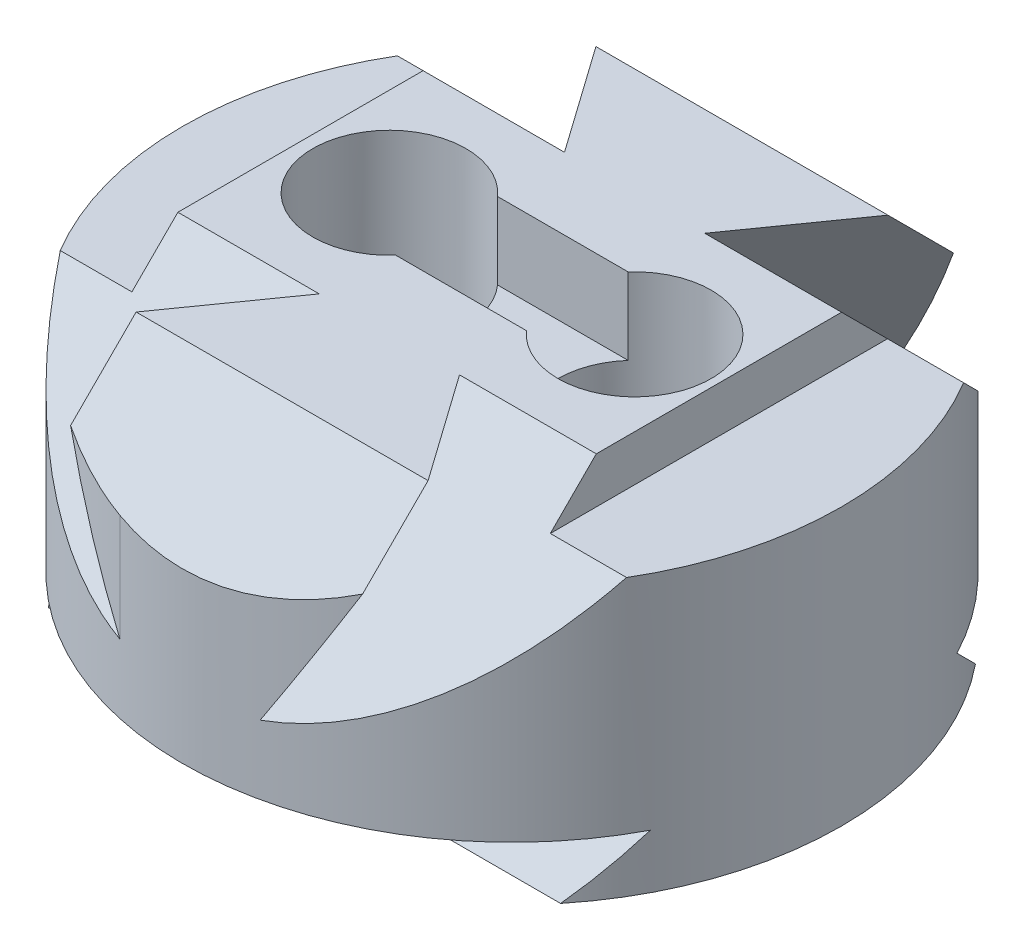
SolidWorks part; units mm, degrees
ref_plane "Front Plane" through (0, 0, 0) normal (0, 0, 1) x (1, 0, 0)
ref_plane "Top Plane" through (0, 0, 0) normal (0, 1, 0) x (1, 0, 0)
ref_plane "Right Plane" through (0, 0, 0) normal (1, 0, 0) x (0, 0, -1)
sketch "Sketch1" plane through (0, 0, 0) normal (0, 1, 0) x (1, 0, 0)
  circle A0 centre (0, 0) radius 21.5
  dimension "D1" = 43
extrude "Boss-Extrude1" add sketch "Sketch1" against normal blind 4
sketch "Sketch2" plane through (0, 0, 0) normal (0, 1, 0) x (1, 0, 0)
  circle A0 centre (0, 0) radius 5.875
  dimension "D1" = 11.75
extrude "Boss-Extrude2" add sketch "Sketch2" along normal blind 65
sketch "Sketch3" plane through (0, 0, 0) normal (0, 1, 0) x (1, 0, 0)
  line L0 (0, 0) -> (0, 21.5) construction
  line L1 (0, 21.5) -> (0, -21.5) construction
  circle A0 centre (0, 0) radius 21.5 construction
ref_plane "Plane1" through (0, 15.5, 0) normal (0, 1, 0) x (1, 0, 0)
sketch "Sketch5" plane through (0, 0, 0) normal (1, 0, 0) x (0, 0, -1)
  line L4 (21.5, 0) -> (-21.5, 0) construction
  line L5 (6, 0) -> (0, 0) construction
  line L8 (21.5, 0) -> (0, 0)
  line L10 (-21.5, 0) -> (0, 0)
  line L11 (21.5, 0) -> (6, 15.5)
  line L12 (23.65, 15.5) -> (-23.65, 15.5) construction
  line L13 (6, 15.5) -> (-6, 15.5)
  line L14 (-6, 15.5) -> (-21.5, 0)
  dimension "D1" = 21.5
  dimension "D2" = 15.5
  dimension "D3" = 15.5
extrude "Boss-Extrude3" add sketch "Sketch5" along normal up to surface and the other way up to surface up to face at (0, -4, 21.5) other way up to face at (0, -4, 21.5)
ref_plane "Plane2" through (0, 4.75, -4.75) normal (0, 0.7071, -0.7071) x (-1, 0, 0)
ref_plane "Plane3" through (0, 4.75, 4.75) normal (0, -0.7071, -0.7071) x (-1, 0, 0)
sketch "Sketch6" plane through (0, 4.75, 4.75) normal (0, -0.7071, -0.7071) x (-1, 0, 0)
  line L0 (0, 15.2028) -> (4.5753, 15.2028)
  line L1 (20.6458, 15.2028) -> (-20.6458, 15.2028) construction
  line L2 (4.5753, 15.2028) -> (9.525, 20.1525)
  line L3 (9.525, 20.1525) -> (0, 20.1525)
  line L4 (0, 20.1525) -> (-9.525, 20.1525)
  line L5 (-9.525, 20.1525) -> (-4.5753, 15.2028)
  line L6 (-4.5753, 15.2028) -> (0, 15.2028)
  dimension "D1" = 7
  dimension "D2" = 45
  dimension "D3" = 45
  dimension "D4" = 9.525
ref_plane "Plane4" through (0, 0, 6) normal (0, 0, 1) x (1, 0, 0)
ref_plane "Plane5" through (0, 0, -6) normal (0, 0, 1) x (1, 0, 0)
sketch "Sketch10" plane through (0, 4.75, -4.75) normal (0, 0.7071, -0.7071) x (-1, 0, 0)
  line L14 (0, 15.2028) -> (-4.5753, 15.2028)
  line L15 (20.6458, 15.2028) -> (-20.6458, 15.2028) construction
  line L16 (-4.5753, 15.2028) -> (-9.525, 20.1525)
  line L18 (9.525, 20.1525) -> (4.5753, 15.2028)
  line L19 (4.5753, 15.2028) -> (0, 15.2028)
  line L20 (9.525, 20.1525) -> (0, 20.1525)
  line L21 (0, 20.1525) -> (-9.525, 20.1525)
  dimension "D1" = 45
  dimension "D2" = 9.525
  dimension "D3" = 7
  dimension "D4" = 45
sketch "Sketch11" plane through (0, 0, 6) normal (0, 0, 1) x (1, 0, 0)
  line L0 (0, 65) -> (0, 15.5) construction
  line L1 (5.875, 65) -> (-5.875, 65) construction
  line L2 (0, 65) -> (0, 15.5) construction
sketch "Sketch12" plane through (0, 15.5, 0) normal (0, 1, 0) x (1, 0, 0)
  line L0 (-20.6458, 6) -> (20.6458, 6)
  line L1 (20.6458, -6) -> (-20.6458, -6)
  arc A0 (-20.6458, 6) -> (-20.6458, -6) centre (0, 0) ccw
  arc A2 (20.6458, 6) -> (20.6458, -6) centre (0, 0) cw
extrude "Boss-Extrude12" add sketch "Sketch6" along normal up to surface (21.9203 mm away) contours L3 L4 L5 L6 L0 L2
sketch "Sketch14" plane through (0, 15.5, 0) normal (0, 1, 0) x (1, 0, 0)
  circle A0 centre (0, 0) radius 5.875
  dimension "D1" = 11.75
ref_plane "Plane7" through (0, -4, 0) normal (0, -1, 0) x (-1, 0, 0)
sketch "Sketch17" plane through (0, 0, 0) normal (0, 0, 1) x (1, 0, 0)
  line L1 (-23.65, -4) -> (23.65, -4) construction
  line L2 (0, -4) -> (5, -4)
  line L3 (0, -4) -> (0, 6)
  line L4 (0, 6) -> (5, -4)
extrude "Boss-Extrude13" add sketch "Sketch10" against normal up to surface (13.8239 mm away) contours L21 L16 L14 L19 L18 L20
extrude "Cut-Extrude3" cut sketch "Sketch14" along normal blind 10 and the other way blind 2 flip side to cut contours A0
ref_plane "Plane8" through (0, 13.5, 0) normal (0, 1, 0) x (1, 0, 0)
sketch "Sketch18" plane through (0, 0, 0) normal (1, 0, 0) x (0, 0, -1)
  line L0 (0, -4) -> (21.5, -4)
  line L1 (-23.65, -4) -> (23.65, -4) construction
  line L2 (21.5, -4) -> (21.5, 7) construction
  line L3 (21.5, -4) -> (0, -49)
  line L4 (0, -49) -> (0, -4)
  dimension "D1" = 45
sketch "Sketch19" plane through (0, 13.5, 0) normal (0, 1, 0) x (1, 0, 0)
  line L0 (0, 0) -> (11, 0) construction
  line L1 (0, 21.5) -> (0, -21.5) construction
  line L2 (11, 0) -> (11, 8)
  line L3 (19.9562, 8) -> (4.5753, 8) construction
  line L4 (11, 0) -> (11, -8)
  line L5 (4.5753, -8) -> (19.9562, -8) construction
  line L6 (0, 0) -> (-11, 0) construction
  line L7 (-11, 0) -> (-11, 8)
  line L8 (-4.5753, 8) -> (-19.9562, 8) construction
  line L9 (-11, 0) -> (-11, -8)
  line L10 (-19.9562, -8) -> (-4.5753, -8) construction
sketch "Sketch20" plane through (0, 0, 0) normal (0, 0, 1) x (1, 0, 0)
  line L0 (0, 13.5) -> (0, 25.5)
  line L1 (0, 13.5) -> (-11, 13.5) construction
  line L2 (0, 13.5) -> (11, 13.5) construction
  line L3 (0, 65) -> (0, 15.5) construction
  line L4 (0, 25.5) -> (-11, 13.5)
  line L5 (0, 25.5) -> (11, 13.5)
  line L6 (-5.875, 65) -> (-5.875, 13.5) construction
  line L7 (5.875, 13.5) -> (5.875, 65) construction
  line L8 (11, 13.5) -> (21.5, 2.0455)
  line L9 (21.5, -4) -> (21.5, 13.5) construction
  point P11 (-5.875, 19.0909)
  point P15 (5.875, 19.0909)
ref_plane "Plane9" through (0, 13.5, 0) normal (-0.6757, -0.7372, 0) x (0, 0, 1)
ref_plane "Plane10" through (0, 13.5, 0) normal (0.6757, -0.7372, 0) x (0, 0, -1)
ref_plane "Plane11" through (6.8269, 7.4475, 0) normal (-0.6757, -0.7372, 0) x (0, 0, 1)
sketch "Sketch22" plane through (6.8269, 7.4475, 0) normal (-0.6757, -0.7372, 0) x (0, 0, 1)
  line L0 (0, 17.231) -> (15, 17.231)
  line L1 (15, 17.231) -> (15, 27.3886)
  line L2 (15, 27.3886) -> (-15, 27.3886)
  line L3 (-15, 27.3886) -> (-15, 17.231)
  line L4 (-15, 17.231) -> (0, 17.231)
ref_plane "Plane12" through (-6.8269, 7.4475, 0) normal (0.6757, -0.7372, 0) x (-0.7372, -0.6757, 0)
sketch "Sketch23" plane through (-6.8269, 7.4475, 0) normal (0.6757, -0.7372, 0) x (-0.7372, -0.6757, 0)
  line L0 (-17.231, 0) -> (-17.231, 15)
  line L1 (-17.231, 15) -> (-27.231, 15)
  line L2 (-27.231, 15) -> (-27.231, -15)
  line L3 (-27.231, -15) -> (-17.231, -15)
  line L4 (-17.231, -15) -> (-17.231, 0)
sketch "Sketch24" plane through (0, 0, 0) normal (0, 0, 1) x (1, 0, 0)
  line L0 (0, -4) -> (10, -4)
  line L1 (0, -4) -> (0, -49) construction
  line L2 (0, -49) -> (0, -4) construction
  line L3 (-23.65, -4) -> (23.65, -4) construction
  line L4 (10, -4) -> (13.5355, -7.5355)
  line L6 (0, -4) -> (-10, -4)
  line L7 (-10, -4) -> (-13.5355, -7.5355)
  line L8 (-13.5355, -7.5355) -> (13.5355, -7.5355)
  dimension "D1" = 10
  dimension "D2" = 10
  dimension "D3" = 5
  dimension "D4" = 45
  dimension "D5" = 5
sketch "Sketch29" plane through (0, 65, 0) normal (0, 1, 0) x (1, 0, 0)
  circle A0 centre (0, 0) radius 7.5081
  dimension "D1" = 15.0162
extrude "Cut-Extrude9" cut sketch "Sketch29" along direction (0, 1, 0) on the side against the normal up to surface (51.5 mm away)
sketch "Sketch30" plane through (0, 13.5, 0) normal (0, 1, 0) x (1, 0, 0)
  line L0 (-23.65, 0) -> (23.65, 0) construction
  circle A0 centre (-8, 0) radius 5
  circle A1 centre (8, 0) radius 5
  dimension "D1" = 10
  dimension "D2" = 10
  dimension "D3" = 8
  dimension "D4" = 8
extrude "Cut-Extrude10" cut sketch "Sketch30" against normal blind 9.8
sketch "Sketch31" plane through (0, 0, -6) normal (0, 0, 1) x (1, 0, 0)
  line L0 (-19.9562, 13.5) -> (-21.5, 13.5) construction
  line L1 (21.5, 13.5) -> (13.5, 13.5)
  line L2 (21.5, 13.5) -> (21.5, 10.5)
  line L3 (21.5, 10.5) -> (13.5, 10.5)
  line L4 (13.5, 13.5) -> (13.5, 10.5)
  line L5 (-21.5, 13.5) -> (-13.8, 13.5)
  line L6 (-21.5, 13.5) -> (-21.5, 10.5)
  line L7 (-21.5, 10.5) -> (-13.8, 10.5)
  line L8 (-13.8, 13.5) -> (-13.8, 10.5)
  dimension "D1" = 8
  dimension "D2" = 3
  dimension "D3" = 7.7
  dimension "D4" = 3
extrude "Cut-Extrude13" cut sketch "Sketch31" against normal through all both and the other way through all
sketch "Sketch32" plane through (0, 13.5, 0) normal (0, 1, 0) x (1, 0, 0)
  line L1 (-1.3, 8) -> (1.3, 8)
  line L2 (-1.3, 8) -> (-1.3, -8)
  line L3 (-1.3, -8) -> (1.3, -8)
  line L4 (1.3, 8) -> (1.3, -8)
  line L5 (-1.3, 8) -> (1.3, -8) construction
  line L6 (-1.3, -8) -> (1.3, 8) construction
  point P0 (0, 0)
  dimension "D1" = 16
  dimension "D2" = 2.6
sketch "Sketch33" plane through (0, -4, 0) normal (0, -1, 0) x (1, 0, 0)
  line L0 (0, 0) -> (0, 10)
  line L1 (0, -21.5) -> (0, 21.5) construction
  line L2 (0, 0) -> (0, -10)
  line L3 (0, 0) -> (0, -21.5) construction
  dimension "D1" = 10
  dimension "D2" = 10
sketch "Sketch34" plane through (0, 0, 0) normal (1, 0, 0) x (0, 0, -1)
  line L0 (0, -4) -> (-10, -4)
  line L1 (0, -4) -> (-10, -4) construction
  line L2 (0, -4) -> (10, -4)
  line L3 (0, -4) -> (21.5, -4) construction
  line L4 (-10, -4) -> (-13.5355, -7.5355)
  line L5 (10, -4) -> (13.5355, -7.5355)
  line L6 (-13.5355, -7.5355) -> (13.5355, -7.5355)
  dimension "D1" = 10
  dimension "D2" = 5
  dimension "D3" = 5
  dimension "D4" = 135
  dimension "D5" = 135
extrude "Boss-Extrude14" add sketch "Sketch34" along normal up to surface and the other way up to surface up to face at (0, 5.8617, 0) other way up to face at (0, 5.8617, 0)
sketch "Sketch35" plane through (0, -7.5355, 0) normal (0, -1, 0) x (1, 0, 0)
  circle A0 centre (-8.3844, 0) radius 5.284
  circle A1 centre (10.939, 0) radius 5.1632
sketch "Sketch36" plane through (0, -7.5355, 0) normal (0, -1, 0) x (1, 0, 0)
  circle A0 centre (-8, 0) radius 5
  circle A1 centre (8, 0) radius 5
  dimension "D1" = 10
  dimension "D2" = 10
  dimension "D3" = 8
  dimension "D4" = 8
extrude "Cut-Extrude14" cut sketch "Sketch36" against normal blind 3
sketch "Sketch38" plane through (0, -4.5355, 0) normal (0, -1, 0) x (1, 0, 0)
  circle A0 centre (-8, 0) radius 1.8923
  circle A1 centre (8, 0) radius 1.8923
  dimension "D1" = 3.7846
  dimension "D2" = 3.7846
extrude "Cut-Extrude15" cut sketch "Sketch38" against normal up to next
sketch "Sketch39" plane through (0, 13.5, 0) normal (0, 1, 0) x (1, 0, 0)
  circle A0 centre (0, 0) radius 2.75
  dimension "D1" = 5.5
sketch "Sketch40" plane through (0, 13.5, 0) normal (0, 1, 0) x (1, 0, 0)
  line L1 (-4.2608, 3.3194) -> (4.2608, 3.3194)
  line L2 (-4.2608, 3.3194) -> (-4.2608, -3.3194)
  line L3 (-4.2608, -3.3194) -> (4.2608, -3.3194)
  line L4 (4.2608, 3.3194) -> (4.2608, -3.3194)
  line L5 (-4.2608, 3.3194) -> (4.2608, -3.3194) construction
  line L6 (-4.2608, -3.3194) -> (4.2608, 3.3194) construction
  circle A0 centre (8, 0) radius 5 construction
  point P0 (0, 0)
extrude "Cut-Extrude16" cut sketch "Sketch40" against normal blind 5
